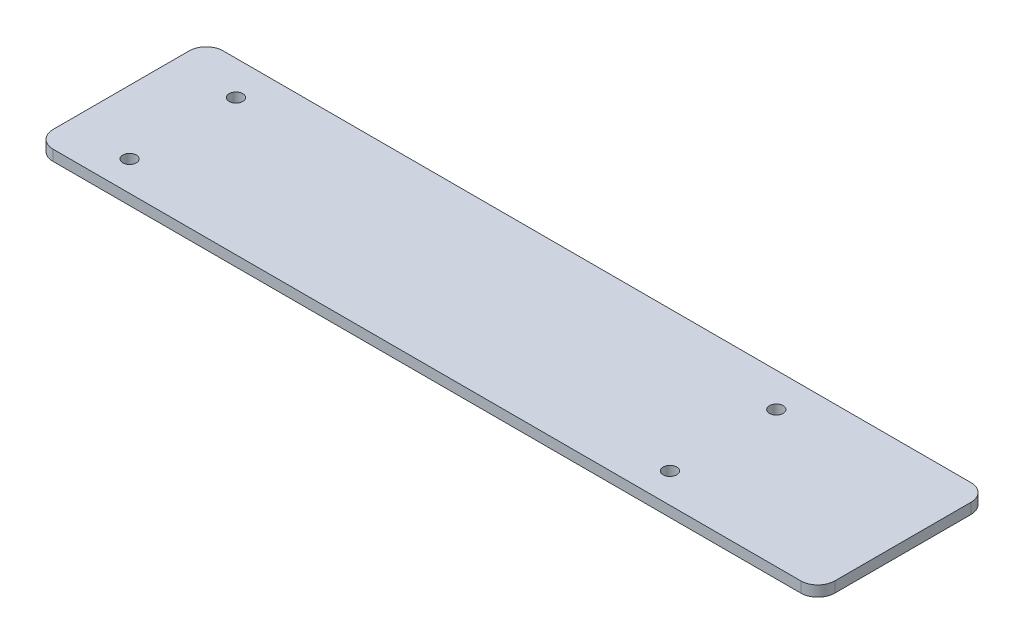
SolidWorks part; units mm, degrees
ref_plane "Front Plane" through (0, 0, 0) normal (0, 0, 1) x (1, 0, 0)
ref_plane "Top Plane" through (0, 0, 0) normal (0, 1, 0) x (1, 0, 0)
ref_plane "Right Plane" through (0, 0, 0) normal (1, 0, 0) x (0, 0, -1)
sketch "Sketch2" plane through (0, 0, 0) normal (0, 1, 0) x (1, 0, 0)
  line L0 (116.6812, -16.51) -> (-116.6813, -16.51) construction
  line L1 (-116.6813, 25.4) -> (116.6812, 25.4)
  line L2 (-116.6813, 25.4) -> (-116.6813, -25.4)
  line L3 (-116.6813, -25.4) -> (116.6812, -25.4)
  line L4 (116.6812, 25.4) -> (116.6812, -25.4)
  line L5 (-116.6813, 25.4) -> (116.6812, -25.4) construction
  line L6 (-116.6813, -25.4) -> (116.6812, 25.4) construction
  line L7 (-97.6312, -16.51) -> (-97.6312, 15.24) construction
  line L8 (63.6588, -16.51) -> (63.6588, 15.24) construction
  circle A0 centre (-97.6312, 15.24) radius 2.032
  circle A1 centre (-97.6312, -16.51) radius 2.032
  circle A2 centre (63.6588, -16.51) radius 2.032
  circle A3 centre (63.6588, 15.24) radius 2.032
  point P0 (0, 0)
  dimension "D5" = 4.064
  dimension "D1" = 233.3625
  dimension "D2" = 50.8
  dimension "D3" = 31.75
  dimension "D4" = 8.89
  dimension "D6" = 53.0225
  dimension "D7" = 214.3125
extrude "Boss-Extrude1" add sketch "Sketch2" along normal blind 3.175
fillet "Fillet1" radius 5.08 4 edges at (116.6812, 1.5875, -25.4) (116.6812, 1.5875, 25.4) (-116.6813, 1.5875, 25.4) (-116.6813, 1.5875, -25.4)
